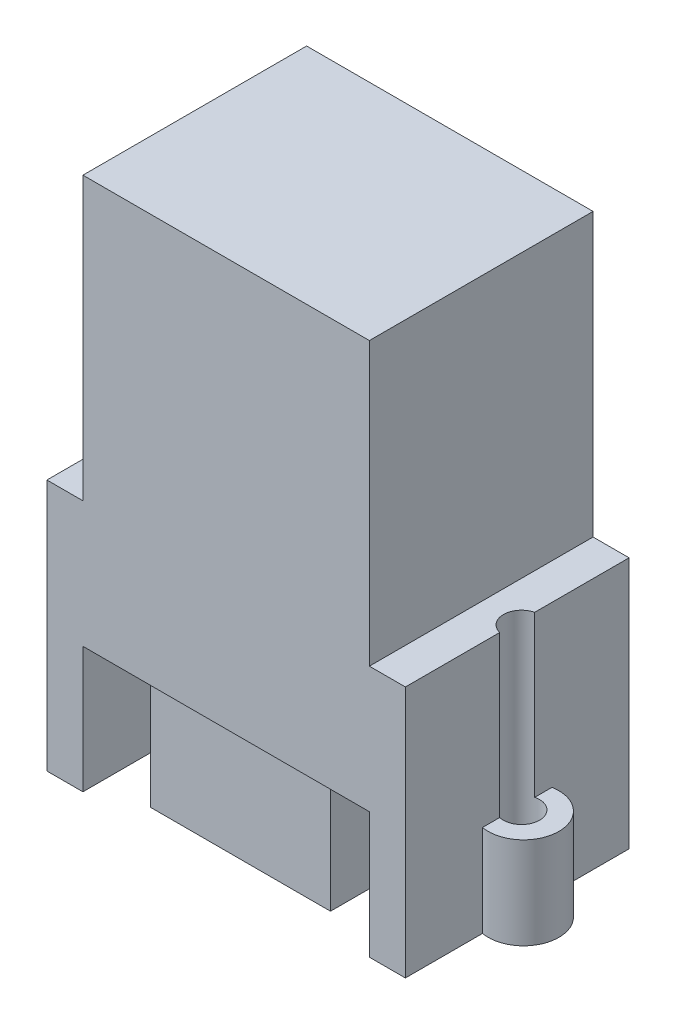
SolidWorks part; units mm, degrees
ref_plane "Front Plane" through (0, 0, 0) normal (0, 0, 1) x (1, 0, 0)
ref_plane "Top Plane" through (0, 0, 0) normal (0, 1, 0) x (1, 0, 0)
ref_plane "Right Plane" through (0, 0, 0) normal (1, 0, 0) x (0, 0, -1)
sketch "Sketch1" plane through (0, 0, 0) normal (0, 1, 0) x (1, 0, 0)
  line L1 (-7.5, -8.125) -> (7.5, -8.125)
  line L2 (-7.5, -8.125) -> (-7.5, 8.125)
  line L3 (-7.5, 8.125) -> (7.5, 8.125)
  line L4 (7.5, -8.125) -> (7.5, 8.125)
  line L5 (-7.5, -8.125) -> (7.5, 8.125) construction
  line L6 (-7.5, 8.125) -> (7.5, -8.125) construction
  point P0 (0, 0)
extrude "Boss-Extrude1" add sketch "Sketch1" against normal blind 10
sketch "Sketch2" plane through (0, 0, 0) normal (0, 1, 0) x (1, 0, 0)
  line L1 (-5.5856, 3.6947) -> (5.5856, 3.6947)
  line L2 (-5.5856, 3.6947) -> (-5.5856, 7.1024)
  line L3 (-5.5856, 7.1024) -> (5.5856, 7.1024)
  line L4 (5.5856, 3.6947) -> (5.5856, 7.1024)
  line L5 (-5.5856, 3.6947) -> (5.5856, 7.1024) construction
  line L6 (-5.5856, 7.1024) -> (5.5856, 3.6947) construction
  line L7 (-5.5856, -5.2866) -> (5.5856, -5.2866)
  line L8 (-5.5856, -5.2866) -> (-5.5856, -1.897)
  line L9 (-5.5856, -1.897) -> (5.5856, -1.897)
  line L10 (5.5856, -5.2866) -> (5.5856, -1.897)
  line L11 (-5.5856, -5.2866) -> (5.5856, -1.897) construction
  line L12 (-5.5856, -1.897) -> (5.5856, -5.2866) construction
  point P0 (0, 5.3986)
  point P5 (0, -3.5918)
extrude "Cut-Extrude1" cut sketch "Sketch2" against normal blind 10
sketch "Sketch3" plane through (0, 0, 0) normal (0, 1, 0) x (1, 0, 0)
  line L1 (-11.935, -9.32) -> (11.935, -9.32)
  line L2 (-11.935, -9.32) -> (-11.935, 9.32)
  line L3 (-11.935, 9.32) -> (11.935, 9.32)
  line L4 (11.935, -9.32) -> (11.935, 9.32)
  line L5 (-11.935, -9.32) -> (11.935, 9.32) construction
  line L6 (-11.935, 9.32) -> (11.935, -9.32) construction
  point P0 (0, 0)
extrude "Boss-Extrude2" add sketch "Sketch3" along normal blind 34
sketch "Sketch4" plane through (-11.935, 0, 0) normal (-1, 0, 0) x (0, 0, 1)
  line L1 (-9.32, 10.5013) -> (9.32, 10.5013)
  line L2 (-9.32, 10.5013) -> (-9.32, -10.5013)
  line L3 (-9.32, -10.5013) -> (9.32, -10.5013)
  line L4 (9.32, 10.5013) -> (9.32, -10.5013)
  line L5 (-9.32, 10.5013) -> (9.32, -10.5013) construction
  line L6 (-9.32, -10.5013) -> (9.32, 10.5013) construction
extrude "Boss-Extrude3" add sketch "Sketch4" along normal blind 3
sketch "Sketch5" plane through (0, -10.5013, 0) normal (0, -1, 0) x (-1, 0, 0)
  line L0 (14.935, 0) -> (14.935, -2.9319)
  line L1 (14.935, 9.32) -> (14.935, -9.32) construction
  line L2 (14.935, -2.9319) -> (15.218, -2.9319)
  line L3 (15.4617, 2.942) -> (14.935, 2.942)
  line L4 (14.935, 2.942) -> (14.935, 0)
  circle A0 centre (15.4617, 0) radius 1.0952
  circle A1 centre (15.4617, 0) radius 2.942
  line M5 (14.935, -9.32) -> (14.935, 9.32)
extrude "Boss-Extrude4" add sketch "Sketch5" against normal blind 7.65 contours A1 L3 L2 M5 | A1 A0
mirror "Mirror1" about plane through (0, 0, 0) normal (1, 0, 0) of "Boss-Extrude3", "Boss-Extrude4"
sketch "Sketch6" plane through (0, -10, 0) normal (0, -1, 0) x (-1, 0, 0)
  line L0 (0, 0) -> (15.29, 0) construction
  circle A0 centre (15.29, 0) radius 1.5
extrude "Cut-Extrude2" cut sketch "Sketch6" against normal through all both and the other way through all
mirror "Mirror2" about plane through (0, 0, 0) normal (1, 0, 0) of "Cut-Extrude2"
